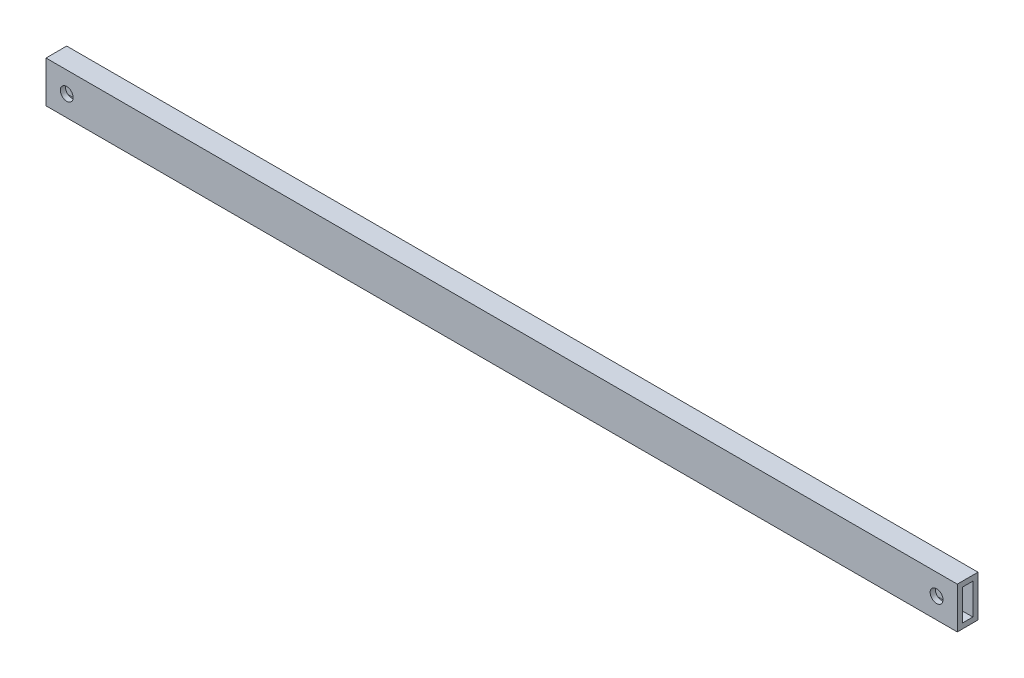
SolidWorks part; units mm, degrees
ref_plane "Front Plane" through (0, 0, 0) normal (0, 0, 1) x (1, 0, 0)
ref_plane "Top Plane" through (0, 0, 0) normal (0, 1, 0) x (1, 0, 0)
ref_plane "Right Plane" through (0, 0, 0) normal (1, 0, 0) x (0, 0, -1)
sketch "Sketch1" plane through (0, 0, 0) normal (1, 0, 0) x (0, 0, -1)
  line L0 (-3.175, -9.525) -> (3.175, -9.525)
  line L1 (-6.35, -12.7) -> (6.35, -12.7)
  line L2 (-6.35, -12.7) -> (-6.35, 12.7)
  line L3 (-6.35, 12.7) -> (6.35, 12.7)
  line L4 (6.35, -12.7) -> (6.35, 12.7)
  line L5 (3.175, -9.525) -> (3.175, 9.525)
  line L6 (-3.175, 9.525) -> (3.175, 9.525)
  line L7 (-3.175, -9.525) -> (-3.175, 9.525)
  dimension "D1" = 25.4
  dimension "D2" = 12.7
  dimension "D3" = 3.175
extrude "Boss-Extrude1" add sketch "Sketch1" along normal blind 558.8
sketch "Sketch2" plane through (0, 0, 6.35) normal (0, 0, 1) x (1, 0, 0)
  line L0 (546.1, 0) -> (546.1, -12.7) construction
  line L2 (558.8, -12.7) -> (0, -12.7) construction
  line L4 (546.1, 0) -> (546.1, 12.7) construction
  line L5 (558.8, 12.7) -> (0, 12.7) construction
  line L6 (279.4, -12.7) -> (279.4, 12.7) construction
  circle A1 centre (546.1, 0) radius 3.3528
  circle A2 centre (12.7, 0) radius 3.3528
extrude "Cut-Extrude1" cut sketch "Sketch2" against normal through all both and the other way through all
sketch "Sketch3" plane through (0, 0, 6.35) normal (0, 0, 1) x (1, 0, 0)
  circle A0 centre (546.1, 0) radius 3.937
  circle A1 centre (12.7, 0) radius 3.937
  dimension "D1" = 7.874
  dimension "D2" = 7.874
extrude "Cut-Extrude2" cut sketch "Sketch3" against normal up to next
